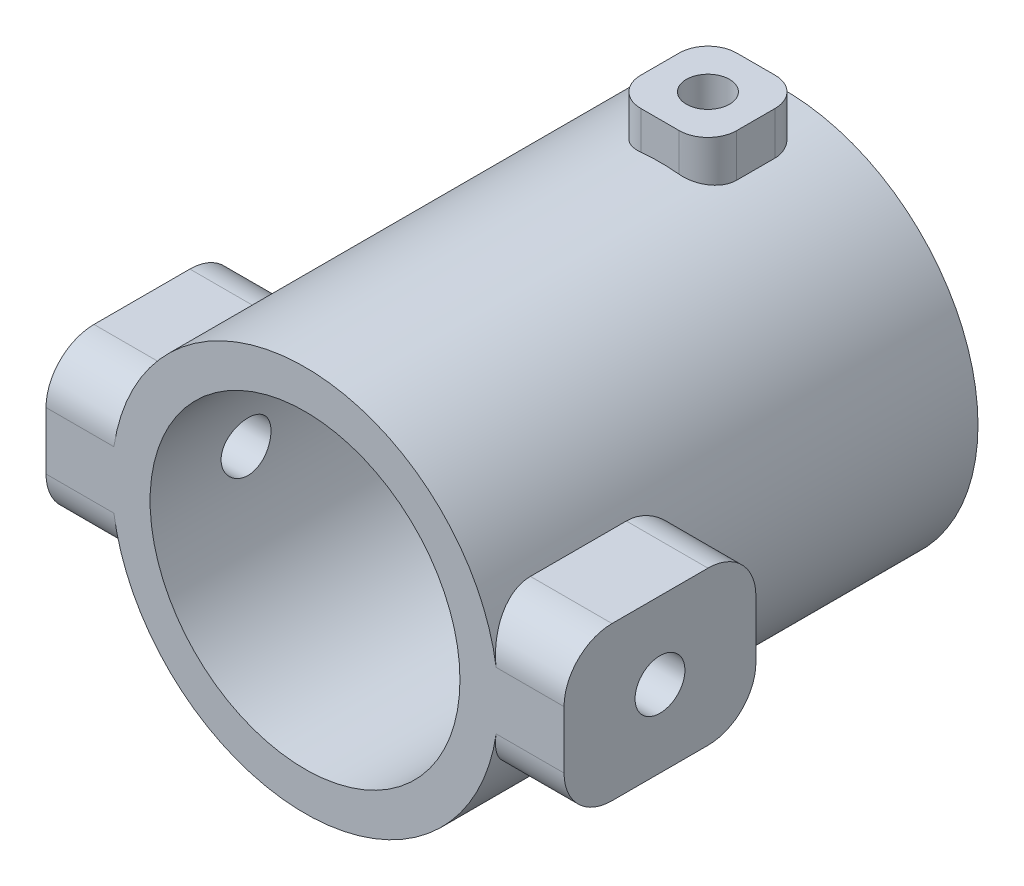
SolidWorks part; units mm, degrees
ref_plane "Plan de face" through (0, 0, 0) normal (0, 0, 1) x (1, 0, 0)
ref_plane "Plan de dessus" through (0, 0, 0) normal (0, 1, 0) x (1, 0, 0)
ref_plane "Plan de droite" through (0, 0, 0) normal (1, 0, 0) x (0, 0, -1)
sketch "Esquisse1" plane through (0, 0, 0) normal (0, 0, 1) x (1, 0, 0)
  circle A0 centre (0, 0) radius 16.15
  circle A1 centre (0, 0) radius 20.15
  dimension "D1" = 32.3
  dimension "D2" = 4
extrude "Boss.-Extru.1" add sketch "Esquisse1" along normal blind 50
sketch "Esquisse2" plane through (0, 0, 50) normal (0, 0, 1) x (1, 0, 0)
  line L0 (0, 0) -> (0, 20.15) construction
  line L1 (0, 0) -> (-20.15, 0) construction
  line L2 (-17, -8) -> (-17, 8)
  line L3 (-17, 8) -> (-27, 8)
  line L4 (-27, 8) -> (-27, -8)
  line L5 (-17, -8) -> (-27, -8)
  line L6 (17, -8) -> (27, -8)
  line L7 (27, 8) -> (27, -8)
  line L8 (17, 8) -> (27, 8)
  line L9 (17, -8) -> (17, 8)
  circle A0 centre (0, 0) radius 20.15 construction
  point P12 (-27, 0)
  point P13 (-17, 0)
  point P17 (17, 0)
  point P18 (27, 0)
  dimension "D1" = 17
  dimension "D2" = 16
  dimension "D3" = 10
extrude "Boss.-Extru.2" add sketch "Esquisse2" against normal blind 20
sketch "Esquisse3" plane through (-27, 0, 0) normal (-1, 0, 0) x (0, 0, 1)
  line L0 (30, 0) -> (50, 0) construction
  line L1 (30, 8) -> (30, -8) construction
  line L2 (50, 8) -> (50, -8) construction
  circle A0 centre (40, 0) radius 2.6
  dimension "D1" = 5.2
extrude "Enlèv. mat.-Extru.1" cut sketch "Esquisse3" against normal through all both and the other way through all
fillet "Congé1" radius 5 8 edges at (22.7469, 8, 30) (22.7469, -8, 30) (22.7469, -8, 50) (22.7469, 8, 50) (-22.7469, -8, 30) (-22.7469, 8, 30) (-22.7469, 8, 50) (-22.7469, -8, 50)
sketch "Esquisse5" plane through (0, 0, 0) normal (1, 0, 0) x (0, 0, -1)
  line L0 (0, 0) -> (-3, 0) construction
  line L1 (-3, 0) -> (-3, 18) construction
  line L2 (-3, 18) -> (-3, 24)
  line L3 (-3, 24) -> (-13, 24)
  line L4 (-13, 24) -> (-13, 18)
  line L5 (-13, 18) -> (-3, 18)
  dimension "D1" = 3
  dimension "D2" = 10
  dimension "D3" = 6
  dimension "D4" = 18
extrude "Boss.-Extru.3" add sketch "Esquisse5" along normal blind 5 and the other way blind 5
sketch "Esquisse4" plane through (0, 0, 0) normal (0, 1, 0) x (1, 0, 0)
  line L0 (0, 0) -> (0, -8) construction
  circle A0 centre (0, -8) radius 2.25
  dimension "D1" = 4.5
  dimension "D2" = 8
extrude "Enlèv. mat.-Extru.2" cut sketch "Esquisse4" along normal through all
fillet "Congé2" radius 3 4 edges at (-5, 21.7599, 3) (-5, 21.7599, 13) (5, 21.7599, 13) (5, 21.7599, 3)
